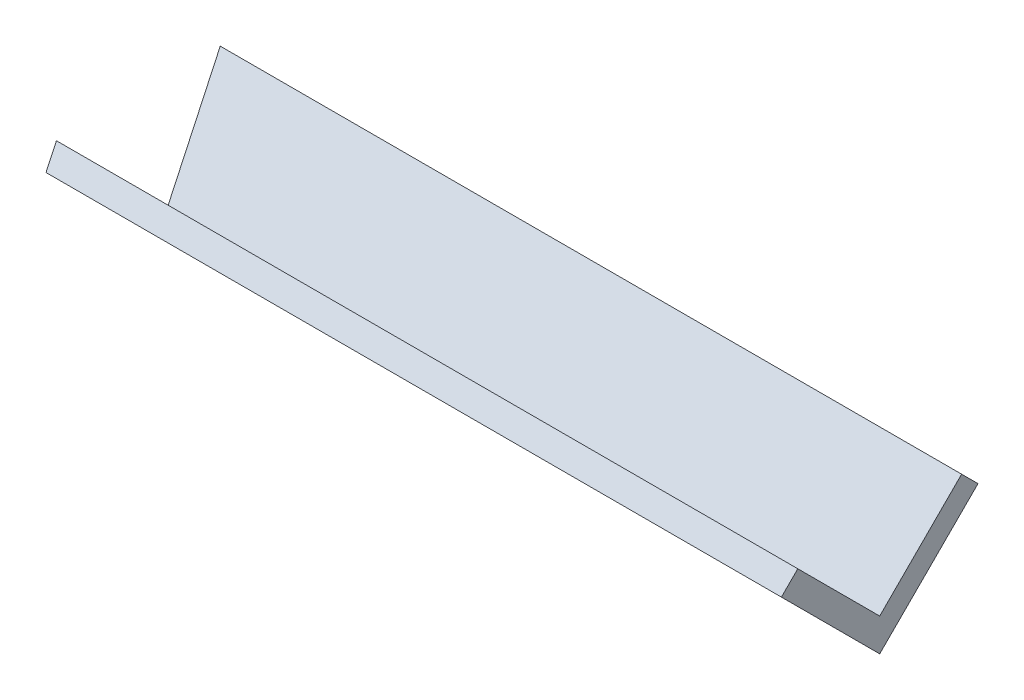
SolidWorks part; units mm, degrees
ref_plane "Front Plane" through (0, 0, 0) normal (0, 0, 1) x (1, 0, 0)
ref_plane "Top Plane" through (0, 0, 0) normal (0, 1, 0) x (1, 0, 0)
ref_plane "Right Plane" through (0, 0, 0) normal (1, 0, 0) x (0, 0, -1)
sketch "Sketch1" plane through (0, 0, 0) normal (1, 0, 0) x (0, 0, -1)
  line L0 (0, 0) -> (-13.4704, 13.4704)
  line L1 (-13.4704, 13.4704) -> (-11.2253, 15.7154)
  line L2 (-11.2253, 15.7154) -> (0, 4.4901)
  line L3 (0, 4.4901) -> (11.2253, 15.7154)
  line L4 (11.2253, 15.7154) -> (13.4704, 13.4704)
  line L5 (13.4704, 13.4704) -> (0, 0)
  dimension "D1" = 19.05
  dimension "D2" = 3.175
extrude "Boss-Extrude1" add sketch "Sketch1" along normal blind 101.6
ref_plane "Plane1" through (5.0508, 1.8384, 0) normal (-0.9397, -0.342, 0) x (0, 0, -1)
sketch "Sketch2" plane through (5.0508, 1.8384, 0) normal (-0.9397, -0.342, 0) x (0, 0, -1)
  line L0 (0, 1.9563) -> (13.4704, -12.3785)
  line L1 (-13.4704, -14.7677) -> (13.4704, -14.7677)
  line L2 (-13.4704, -14.7677) -> (-13.4704, 1.9563)
  line L3 (-13.4704, 1.9563) -> (13.4704, 1.9563)
  line L4 (13.4704, -14.7677) -> (13.4704, 1.9563)
  line L5 (0, 1.9563) -> (13.4704, -12.3785) construction
extrude "Cut-Extrude1" cut sketch "Sketch2" along normal through all
